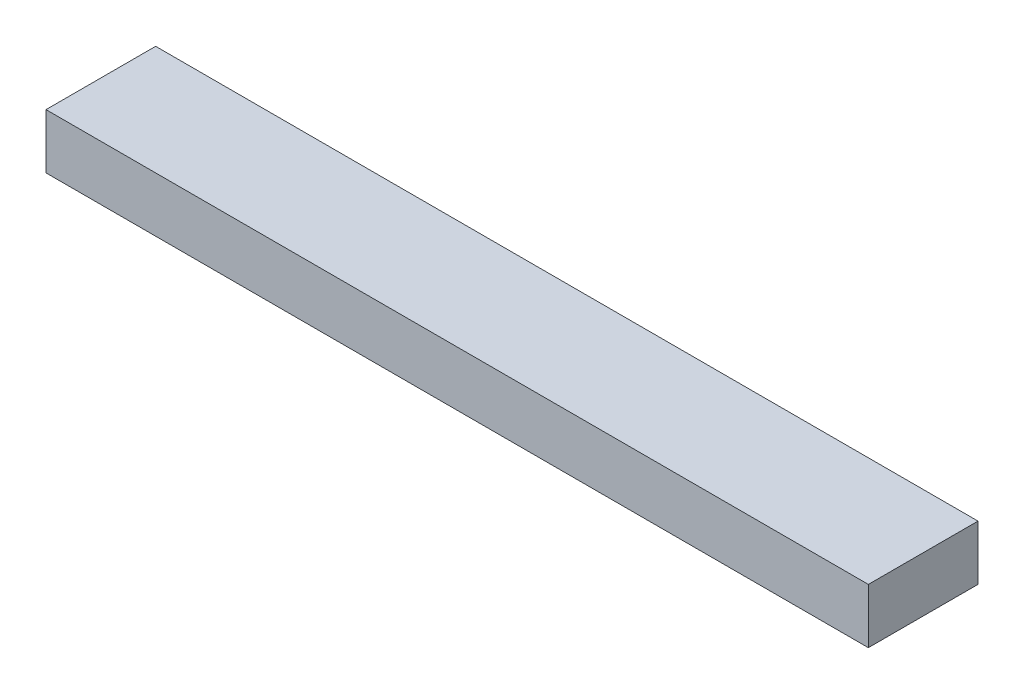
SolidWorks part; units mm, degrees
ref_plane "Front Plane" through (0, 0, 0) normal (0, 0, 1) x (1, 0, 0)
ref_plane "Top Plane" through (0, 0, 0) normal (0, 1, 0) x (1, 0, 0)
ref_plane "Right Plane" through (0, 0, 0) normal (1, 0, 0) x (0, 0, -1)
sketch "Sketch1" plane through (0, 0, 0) normal (0, 1, 0) x (1, 0, 0)
  line L1 (-75, -10) -> (75, -10)
  line L2 (-75, -10) -> (-75, 10)
  line L3 (-75, 10) -> (75, 10)
  line L4 (75, -10) -> (75, 10)
  line L5 (-75, -10) -> (75, 10) construction
  line L6 (-75, 10) -> (75, -10) construction
  point P0 (0, 0)
  dimension "D1" = 20
  dimension "D2" = 150
extrude "Boss-Extrude1" add sketch "Sketch1" along normal blind 10
